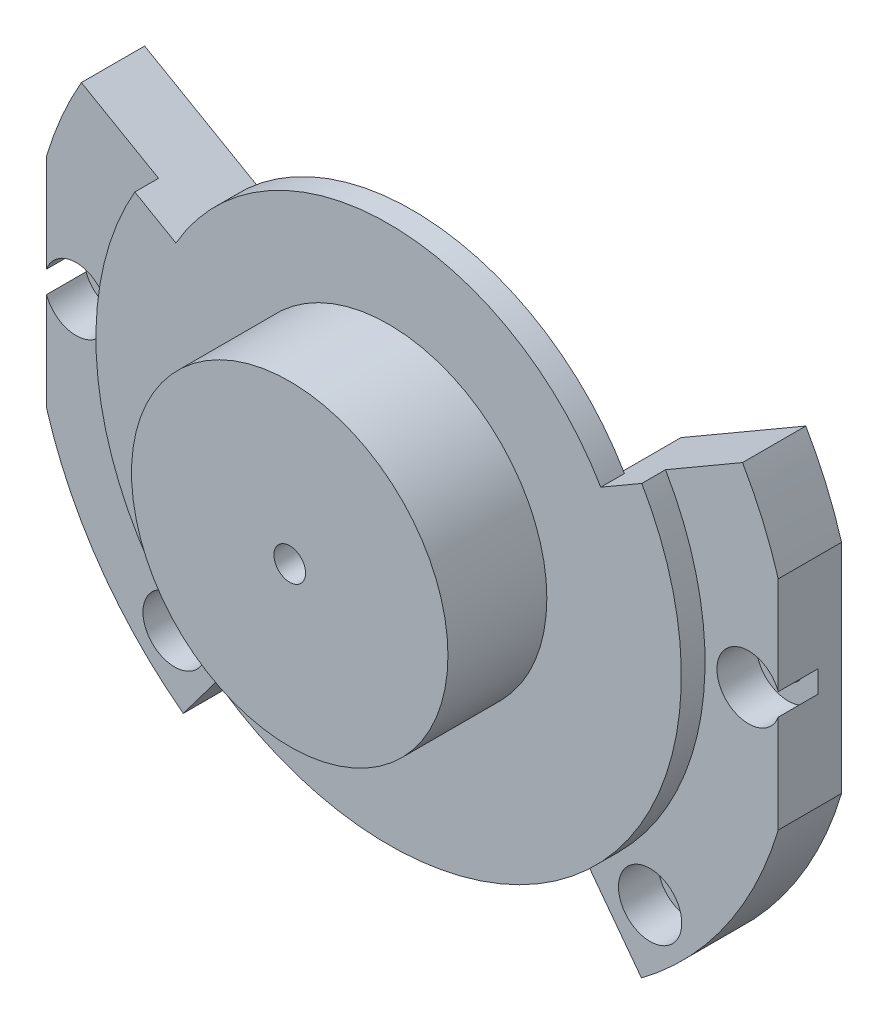
SolidWorks part; units mm, degrees
ref_plane "Front Plane" through (0, 0, 0) normal (0, 0, 1) x (1, 0, 0)
ref_plane "Top Plane" through (0, 0, 0) normal (0, 1, 0) x (1, 0, 0)
ref_plane "Right Plane" through (0, 0, 0) normal (1, 0, 0) x (0, 0, -1)
sketch "Sketch1" plane through (0, 0, 0) normal (0, 0, 1) x (1, 0, 0)
  circle A0 centre (0, 0) radius 48.25
extrude "Boss-Extrude1" add sketch "Sketch1" against normal blind 8 contours A0
sketch "Sketch2" plane through (0, 0, 0) normal (0, 0, 1) x (1, 0, 0)
  line L1 (-63.412, 28.4111) -> (-46.25, 28.4111)
  line L2 (-63.412, 28.4111) -> (-63.412, -28.4111)
  line L3 (-63.412, -28.4111) -> (-46.25, -28.4111)
  line L4 (-46.25, 28.4111) -> (-46.25, -28.4111)
  line L5 (46.25, 28.4111) -> (62.4025, 28.4111)
  line L6 (46.25, 28.4111) -> (46.25, -36.7758)
  line L7 (46.25, -36.7758) -> (62.4025, -36.7758)
  line L8 (62.4025, 28.4111) -> (62.4025, -36.7758)
  dimension "D1" = 92.5
  dimension "D2" = 46.25
extrude "Cut-Extrude1" cut sketch "Sketch2" against normal blind 8 contours L5 L8 L7 L6 | L1 L4 L3 L2
sketch "Sketch3" plane through (0, 0, 0) normal (0, 0, 1) x (1, 0, 0)
  circle A0 centre (0, 0) radius 30
extrude "Cut-Extrude2" cut sketch "Sketch3" against normal blind 8 contours A0
sketch "Sketch4" plane through (0, 0, 0) normal (0, 0, 1) x (1, 0, 0)
  circle A0 centre (-42.5, 0) radius 1.75
  dimension "D1" = 42.5
extrude "Cut-Extrude3" cut sketch "Sketch4" against normal blind 10
pattern_circular "CirPattern1" count 8 every 45 about axis through (0, 0, 0) along (0, 0, 1) of "Cut-Extrude3"
sketch "Sketch8" plane through (0, 0, 0) normal (0, 0, 1) x (1, 0, 0)
  line L0 (-28.9595, 38.5928) -> (0, 0)
  line L1 (0, 0) -> (28.9595, 38.5928)
  arc A0 (46.25, 13.7477) -> (-46.25, 13.7477) centre (0, 0) ccw construction
  arc A1 (-28.9595, 38.5928) -> (28.9595, 38.5928) centre (0, 0) cw
  circle A2 centre (-30.052, 30.052) radius 1.75 construction
  circle A3 centre (30.052, 30.052) radius 1.75 construction
  dimension "D1" = 6
  dimension "D3" = 0
  dimension "D2" = 6
extrude "Cut-Extrude4" cut sketch "Sketch8" against normal blind 10 contours L0 L1 A1
pattern_circular "CirPattern2" count 2 every 180 about axis through (0, 0, 0) along (0, 0, 1) of "Cut-Extrude4"
sketch "Sketch9" plane through (0, 0, 0) normal (0, 0, 1) x (1, 0, 0)
  circle A0 centre (-42.5, 0) radius 4
extrude "Cut-Extrude5" cut sketch "Sketch9" against normal blind 5 contours A0
pattern_circular "CirPattern3" count 8 every 45 about axis through (0, 0, 0) along (0, 0, 1) of "Cut-Extrude5"
sketch "Sketch10" plane through (0, 0, 0) normal (0, 0, 1) x (1, 0, 0)
  circle A0 centre (42.5, 0) radius 4
  circle A1 centre (30.052, 30.052) radius 4
  circle A2 centre (30.052, -30.052) radius 4
extrude "Cut-Extrude6" cut sketch "Sketch10" against normal blind 5
sketch "Sketch11" plane through (0, 0, 0) normal (0, 0, 1) x (1, 0, 0)
  circle A0 centre (0, 0) radius 37
extrude "Boss-Extrude2" add sketch "Sketch11" along normal blind 3 contours A0
sketch "Sketch12" plane through (0, 0, 3) normal (0, 0, 1) x (1, 0, 0)
  circle A0 centre (0, 0) radius 20
extrude "Boss-Extrude3" add sketch "Sketch12" along normal blind 12.5 contours A0
sketch "Sketch13" plane through (0, 0, 15.5) normal (0, 0, 1) x (1, 0, 0)
  circle A0 centre (0, 0) radius 2
extrude "Cut-Extrude8" cut sketch "Sketch13" against normal blind 38
sketch "Sketch14" plane through (0, 0, 0) normal (0, 0, -1) x (-1, 0, 0)
  line L1 (-2.0207, -3.5) -> (2.0207, -3.5)
  line L2 (2.0207, -3.5) -> (4.0415, 0)
  line L3 (4.0415, 0) -> (2.0207, 3.5)
  line L4 (2.0207, 3.5) -> (-2.0207, 3.5)
  line L5 (-2.0207, 3.5) -> (-4.0415, 0)
  line L6 (-4.0415, 0) -> (-2.0207, -3.5)
  circle A0 centre (0, 0) radius 3.5 construction
extrude "Cut-Extrude9" cut sketch "Sketch14" against normal blind 4 contours L4 L5 L6 L1 L2 L3
sketch "Sketch15" plane through (0, 0, 0) normal (0, 0, 1) x (1, 0, 0)
  line L0 (-41.839, 24.0325) -> (0, 0)
  line L1 (0, 0) -> (41.7322, 24.2174)
  arc A0 (-41.839, 24.0325) -> (41.7322, 24.2174) centre (0, 0) cw
  arc A3 (46.25, 13.7477) -> (28.9595, 38.5928) centre (0, 0) ccw construction
  point P4 (41.839, 24.0325)
  dimension "D1" = 120
extrude "Cut-Extrude10" cut sketch "Sketch15" against normal blind 10 contours L0 L1 A0
sketch "Sketch16" plane through (0, 0, 0) normal (0, 0, 1) x (1, 0, 0)
  line L0 (-41.839, 24.0325) -> (-26.881, 15.4406)
  line L1 (26.8124, 15.5594) -> (41.7322, 24.2174)
  arc A0 (-41.839, 24.0325) -> (41.7322, 24.2174) centre (0, 0) cw
  arc A1 (26.8124, 15.5594) -> (-26.881, 15.4406) centre (0, 0) ccw
  point P4 (0, 0)
  dimension "D1" = 120
  dimension "D2" = 31
extrude "Cut-Extrude11" cut sketch "Sketch16" along normal blind 14
